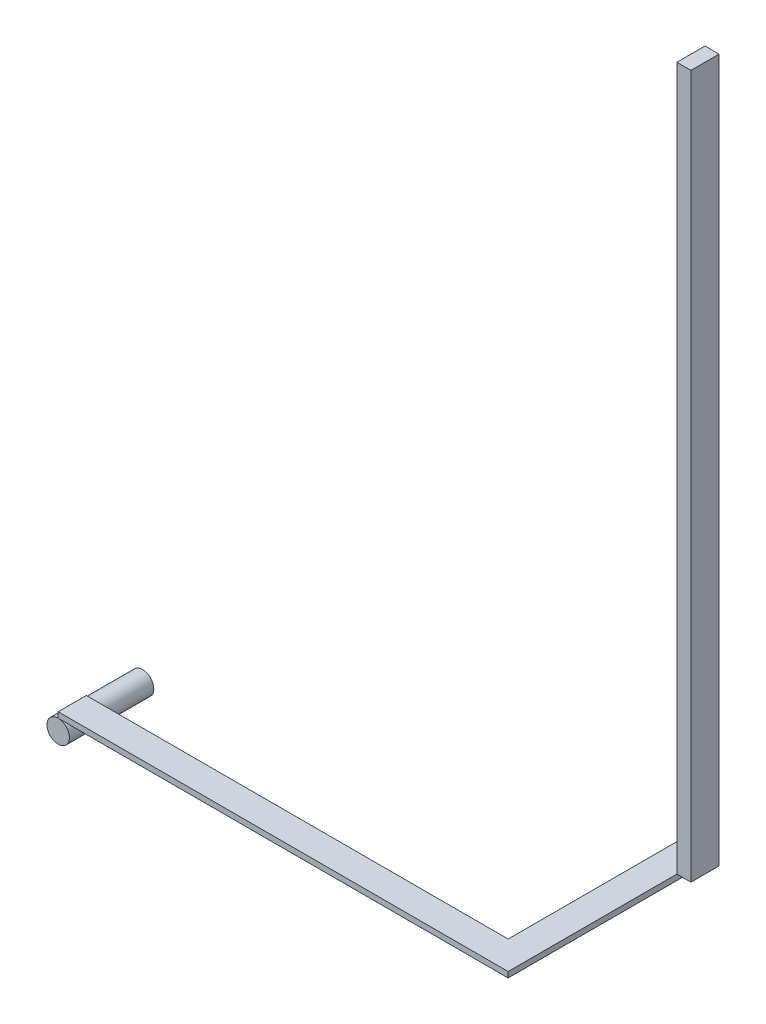
SolidWorks part; units mm, degrees
ref_plane "Front Plane" through (0, 0, 0) normal (0, 0, 1) x (1, 0, 0)
ref_plane "Top Plane" through (0, 0, 0) normal (0, 1, 0) x (1, 0, 0)
ref_plane "Right Plane" through (0, 0, 0) normal (1, 0, 0) x (0, 0, -1)
sketch "Sketch1" plane through (0, 0, 0) normal (0, 0, 1) x (1, 0, 0)
  circle A0 centre (0, 0) radius 4
  dimension "D1" = 8
extrude "Boss-Extrude1" add sketch "Sketch1" along normal blind 30
sketch "Sketch2" plane through (0, 0, 30) normal (0, 0, 1) x (1, 0, 0)
  line L1 (0, 4) -> (160, 4)
  line L2 (0, 4) -> (0, 6)
  line L3 (0, 6) -> (160, 6)
  line L4 (160, 4) -> (160, 6)
  circle A0 centre (0, 0) radius 4 construction
  dimension "D1" = 2
  dimension "D2" = 160
extrude "Boss-Extrude2" add sketch "Sketch2" against normal blind 10 separate body
sketch "Sketch3" plane through (0, 0, 20) normal (0, 0, -1) x (-1, 0, 0)
  line L0 (-160, 6) -> (0, 6) construction
  line L1 (-150, 6) -> (-160, 6)
  line L2 (-150, 6) -> (-150, 4)
  line L3 (-150, 4) -> (-160, 4)
  line L4 (-160, 6) -> (-160, 4)
  line L5 (0, 4) -> (-160, 4) construction
  line L6 (-160, 4) -> (-160, 6) construction
  dimension "D1" = 10
extrude "Boss-Extrude3" add sketch "Sketch3" along normal blind 60
sketch "Sketch5" plane through (160, 0, 0) normal (1, 0, 0) x (0, 0, -1)
  line L1 (40, 6) -> (30, 6)
  line L2 (40, 6) -> (40, 256)
  line L3 (40, 256) -> (30, 256)
  line L4 (30, 6) -> (30, 256)
  dimension "D1" = 10
  dimension "D2" = 250
extrude "Boss-Extrude5" add sketch "Sketch5" along normal blind 5
